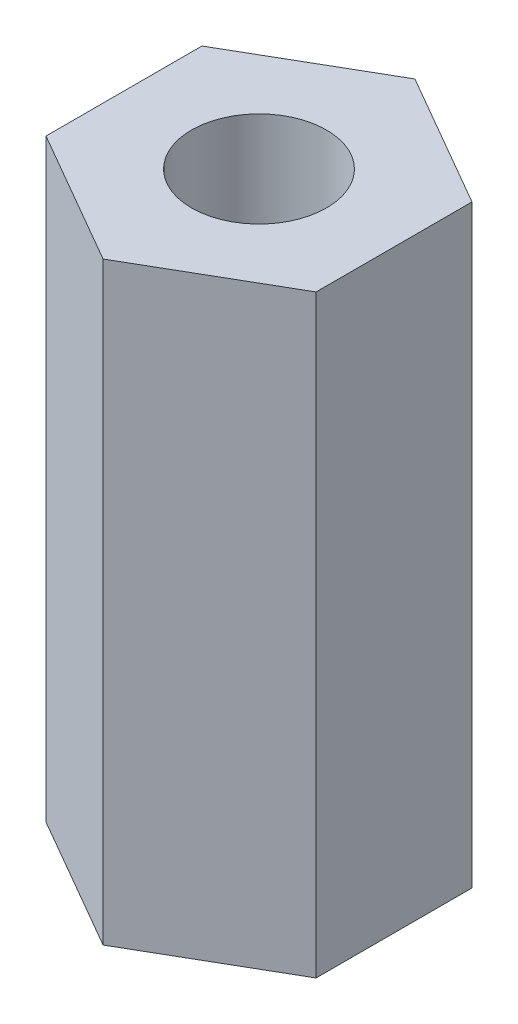
SolidWorks part; units mm, degrees
material "Nylon 101"
ref_plane "Front Plane" through (0, 0, 0) normal (0, 0, 1) x (1, 0, 0)
ref_plane "Top Plane" through (0, 0, 0) normal (0, 1, 0) x (1, 0, 0)
ref_plane "Right Plane" through (0, 0, 0) normal (1, 0, 0) x (0, 0, -1)
sketch "Sketch1" plane through (0, 0, 0) normal (0, 1, 0) x (1, 0, 0)
  line L1 (0, 2.8868) -> (-2.5, 1.4434)
  line L2 (-2.5, 1.4434) -> (-2.5, -1.4434)
  line L3 (-2.5, -1.4434) -> (0, -2.8868)
  line L4 (0, -2.8868) -> (2.5, -1.4434)
  line L5 (2.5, -1.4434) -> (2.5, 1.4434)
  line L6 (2.5, 1.4434) -> (0, 2.8868)
  circle A0 centre (0, 0) radius 2.5 construction
  circle A1 centre (0, 0) radius 1.25
  dimension "D2" = 2.5
  dimension "D1" = 5
extrude "Boss-Extrude1" add sketch "Sketch1" along normal blind 11
